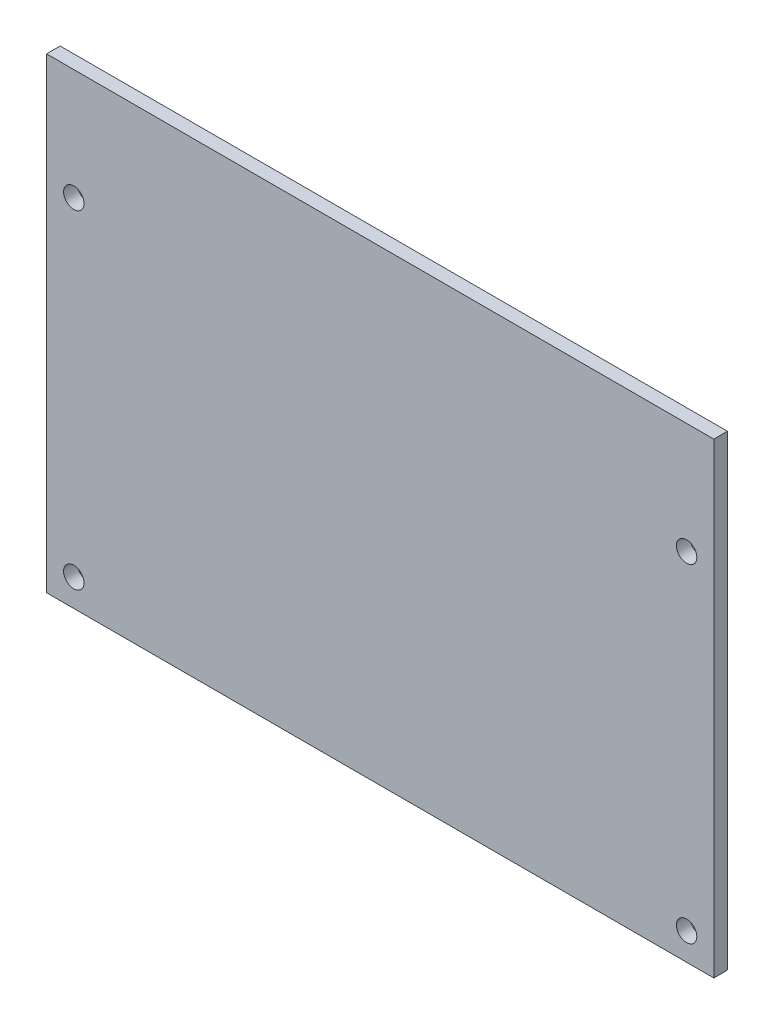
SolidWorks part; units mm, degrees
material "自訂玻璃纖維"
ref_plane "前基準面" through (0, 0, 0) normal (0, 0, 1) x (1, 0, 0)
ref_plane "上基準面" through (0, 0, 0) normal (0, 1, 0) x (1, 0, 0)
ref_plane "右基準面" through (0, 0, 0) normal (1, 0, 0) x (0, 0, -1)
sketch "草圖1" plane through (0, 0, 0) normal (0, 0, 1) x (1, 0, 0)
  line L0 (-61.2328, 41.6881) -> (-61.2328, -26.8542)
  line L1 (-61.2328, -26.8542) -> (36.7672, -26.8542)
  line L2 (-61.2328, 41.6881) -> (36.7672, 41.6881)
  line L3 (36.7672, 41.6881) -> (36.7672, -26.8542)
  circle A0 centre (-57.2328, 25.3958) radius 1.5
  circle A1 centre (-57.2328, -22.8542) radius 1.5
  circle A2 centre (32.7672, -22.8542) radius 1.5
  circle A3 centre (32.7672, 25.3958) radius 1.5
  point P8 (-57.2328, 25.3958)
  dimension "D1" = 3
  dimension "D3" = 90
  dimension "D4" = 90
  dimension "D5" = 4
  dimension "D6" = 4
  dimension "D8" = 4
  dimension "D2" = 4
  dimension "D7" = 4
extrude "填料-伸長1" add sketch "草圖1" along normal blind 2
